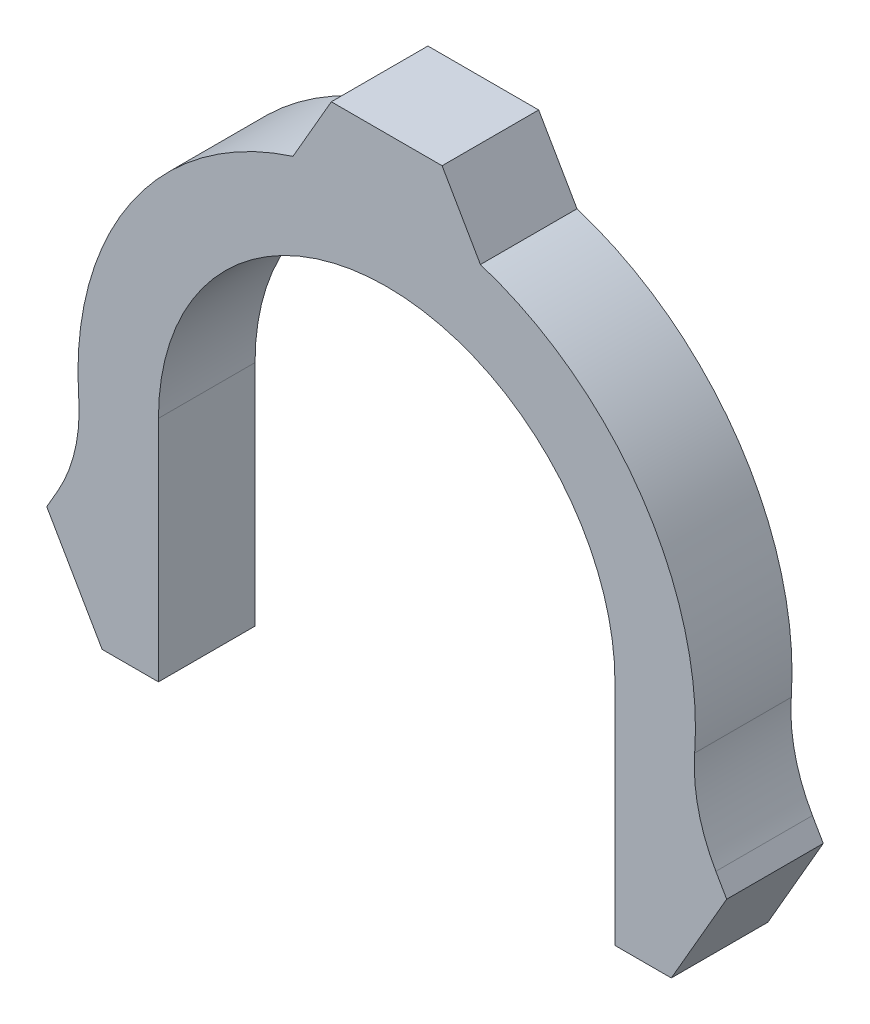
SolidWorks part; units mm, degrees
ref_plane "Front Plane" through (0, 0, 0) normal (0, 0, 1) x (1, 0, 0)
ref_plane "Top Plane" through (0, 0, 0) normal (0, 1, 0) x (1, 0, 0)
ref_plane "Right Plane" through (0, 0, 0) normal (1, 0, 0) x (0, 0, -1)
sketch "Sketch1" plane through (0, 0, 0) normal (0, 0, 1) x (1, 0, 0)
  line L0 (-45.1379, 106.8177) -> (-56.7826, 86.6485)
  line L1 (-94.2571, 21.7407) -> (-73.4969, 21.7407)
  line L2 (3.9813, 21.7407) -> (-4.2445, 35.9881)
  line L3 (-86.0314, 35.9881) -> (-94.2571, 21.7407)
  line L4 (-33.4932, 86.6485) -> (-45.1379, 106.8177)
  line L5 (-16.7789, 50.0997) -> (-16.7789, 21.7407)
  line L6 (-73.4969, 50.0997) -> (-73.4969, 21.7407)
  line L7 (-16.7789, 21.7407) -> (3.9813, 21.7407)
  circle A0 centre (-45.1379, 50.0997) radius 28.359 construction
  arc A1 (-16.7789, 50.0997) -> (-73.4969, 50.0997) centre (-45.1379, 50.0997) ccw
  arc A2 (-56.7826, 86.6485) -> (-83.4016, 47.3972) centre (-45.1379, 50.0997) ccw
  arc A3 (-6.8742, 47.3972) -> (-33.4932, 86.6485) centre (-45.1379, 50.0997) ccw
  circle A4 centre (-45.1379, 50.0997) radius 38.359 construction
  circle A5 centre (-45.1379, 50.0997) radius 28.359 construction
  arc A6 (-4.2445, 35.9881) -> (-6.8742, 47.3972) centre (13.0761, 45.9881) cw
  arc A7 (-83.4016, 47.3972) -> (-86.0314, 35.9881) centre (-103.3519, 45.9881) cw
  point P8 (-6.7789, 50.0997)
  point P12 (-18.0181, 58.3911)
  point P20 (-7.6634, 41.9099)
  dimension "D2" = 20
  dimension "D1" = 10
extrude "Boss-Extrude1" add sketch "Sketch1" along normal blind 12
sketch "Sketch2" plane through (0, 0, 12) normal (0, 0, 1) x (1, 0, 0)
  line L1 (-52.0188, 94.8997) -> (-38.2571, 94.8997)
  line L2 (-81.4254, 23.3514) -> (-86.4463, 32.048) construction
  line L3 (-80.4954, 21.7407) -> (-87.3763, 33.6587)
  line L4 (-3.8295, 32.048) -> (-8.8505, 23.3514) construction
  line L5 (-2.8996, 33.6587) -> (-9.7804, 21.7407)
  line L6 (-16.7789, 21.7407) -> (3.9813, 21.7407) construction
  line L7 (3.9813, 21.7407) -> (-4.2445, 35.9881) construction
  line L8 (-94.2571, 21.7407) -> (-73.4969, 21.7407) construction
  line L9 (-86.0314, 35.9881) -> (-94.2571, 21.7407) construction
  line L10 (-33.4932, 86.6485) -> (-45.1379, 106.8177) construction
  line L11 (-45.1379, 106.8177) -> (-56.7826, 86.6485) construction
  line L12 (-9.7804, 21.7407) -> (3.9813, 21.7407)
  line L13 (3.9813, 21.7407) -> (-2.8996, 33.6587)
  line L14 (-94.2571, 21.7407) -> (-80.4954, 21.7407)
  line L15 (-87.3763, 33.6587) -> (-94.2571, 21.7407)
  line L16 (-38.2571, 94.8997) -> (-45.1379, 106.8177)
  line L17 (-45.1379, 106.8177) -> (-52.0188, 94.8997)
  line L18 (-50.1589, 94.8997) -> (-40.117, 94.8997) construction
extrude "Cut-Extrude1" cut sketch "Sketch2" against normal blind 12
